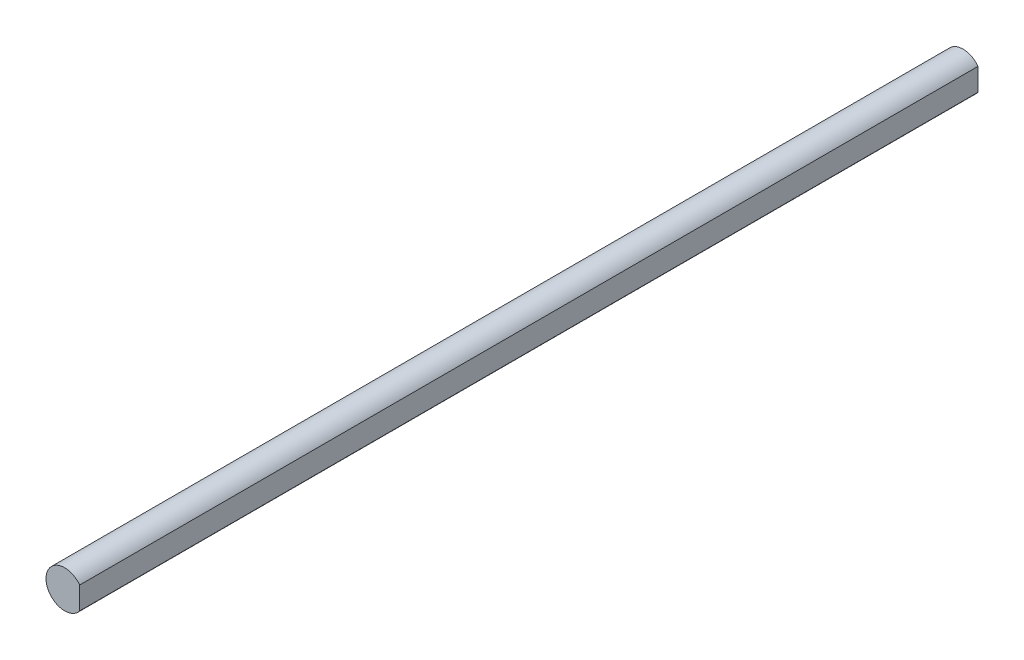
SolidWorks part; units mm, degrees
ref_plane "Plan de face" through (0, 0, 0) normal (0, 0, 1) x (1, 0, 0)
ref_plane "Plan de dessus" through (0, 0, 0) normal (0, 1, 0) x (1, 0, 0)
ref_plane "Plan de droite" through (0, 0, 0) normal (1, 0, 0) x (0, 0, -1)
sketch "Esquisse1" plane through (0, 0, 0) normal (0, 0, 1) x (1, 0, 0)
  circle A0 centre (0, 0) radius 3.175
  dimension "D1" = 6.35
extrude "Boss.-Extru.1" add sketch "Esquisse1" along normal blind 152.4
sketch "Esquisse2" plane through (0, 0, 0) normal (0, 0, -1) x (-1, 0, 0)
  line L0 (-4.7939, 2.4947) -> (-2.54, 2.4947)
  line L1 (-2.54, 2.4947) -> (-2.54, -3.175)
  line L2 (-2.54, -3.175) -> (-4.7939, -3.175)
  line L3 (-4.7939, -3.175) -> (-4.7939, 2.4947)
  circle A0 centre (0, 0) radius 3.175 construction
  dimension "D1" = 2.54
extrude "Enlèv. mat.-Extru.1" cut sketch "Esquisse2" against normal up to next
